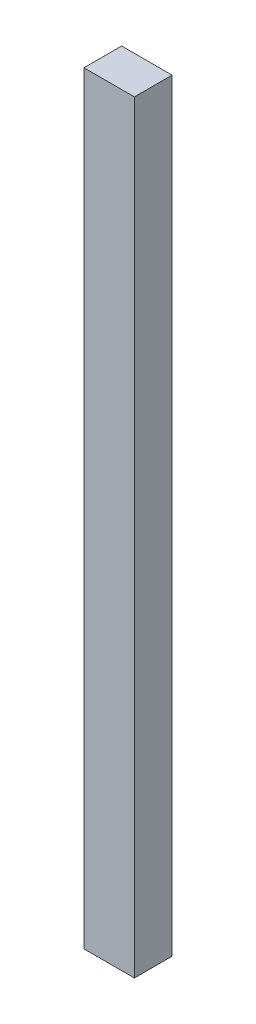
SolidWorks part; units mm, degrees
ref_plane "Front Plane" through (0, 0, 0) normal (0, 0, 1) x (1, 0, 0)
ref_plane "Top Plane" through (0, 0, 0) normal (0, 1, 0) x (1, 0, 0)
ref_plane "Right Plane" through (0, 0, 0) normal (1, 0, 0) x (0, 0, -1)
sketch "Sketch1" plane through (0, 0, 0) normal (0, 1, 0) x (1, 0, 0)
  line L0 (-27.8321, 19.4041) -> (30.9681, 19.4041)
  line L1 (30.9681, 19.4041) -> (30.9681, -24.5001)
  line L2 (30.9681, -24.5001) -> (-27.8321, -24.5001)
  line L3 (-27.8321, -24.5001) -> (-27.8321, 19.4041)
extrude "Boss-Extrude1" add sketch "Sketch1" along normal blind 889
